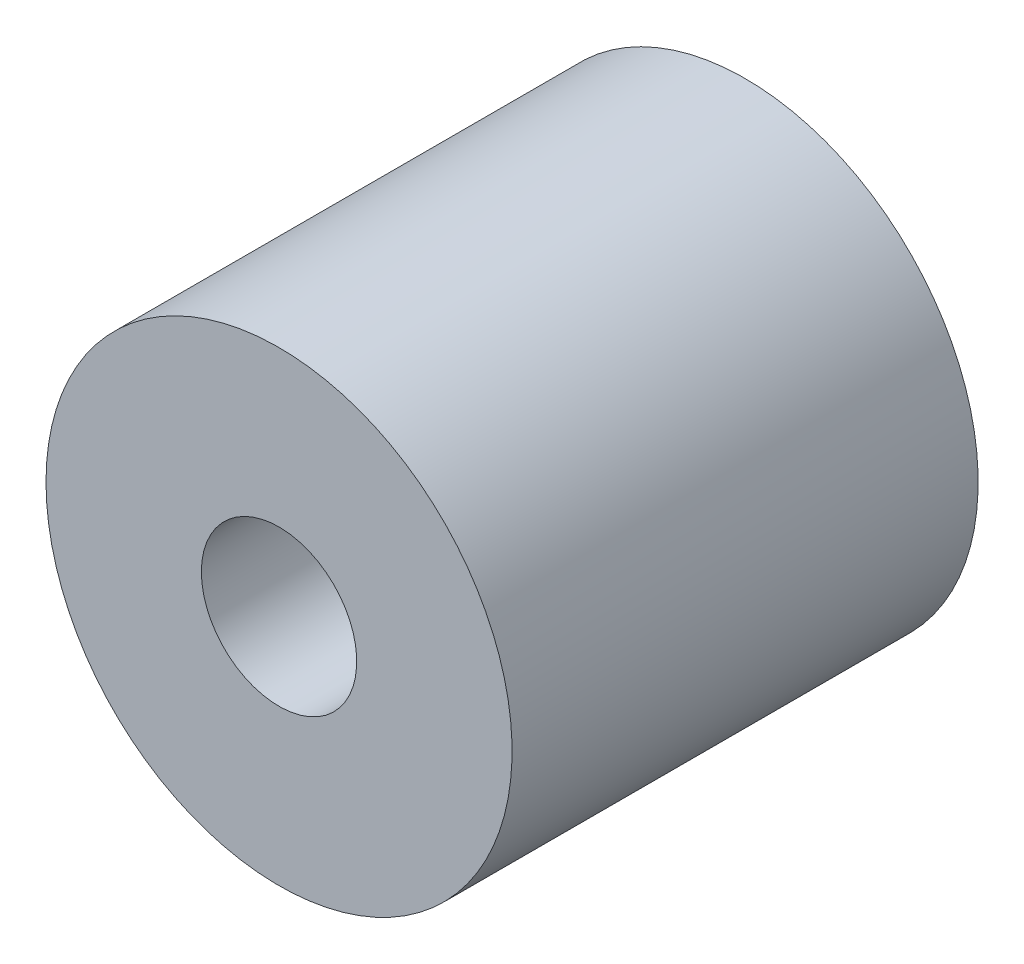
SolidWorks part; units mm, degrees
ref_plane "Front Plane" through (0, 0, 0) normal (0, 0, 1) x (1, 0, 0)
ref_plane "Top Plane" through (0, 0, 0) normal (0, 1, 0) x (1, 0, 0)
ref_plane "Right Plane" through (0, 0, 0) normal (1, 0, 0) x (0, 0, -1)
sketch "AnnulusProfile" plane through (0, 0, 0) normal (0, 1, 0) x (1, 0, 0)
  line L1 (2, 0) -> (6, 0)
  line L2 (2, 0) -> (2, -12)
  line L3 (2, -12) -> (6, -12)
  line L4 (6, 0) -> (6, -12)
  line L5 (0, 0) -> (0, -20) construction
  dimension "inner_radius_mm" = 2
  dimension "outer_radius_mm" = 6
  dimension "height_mm" = 12
revolve "Revolution" add sketch "AnnulusProfile" angle 360 about L5
